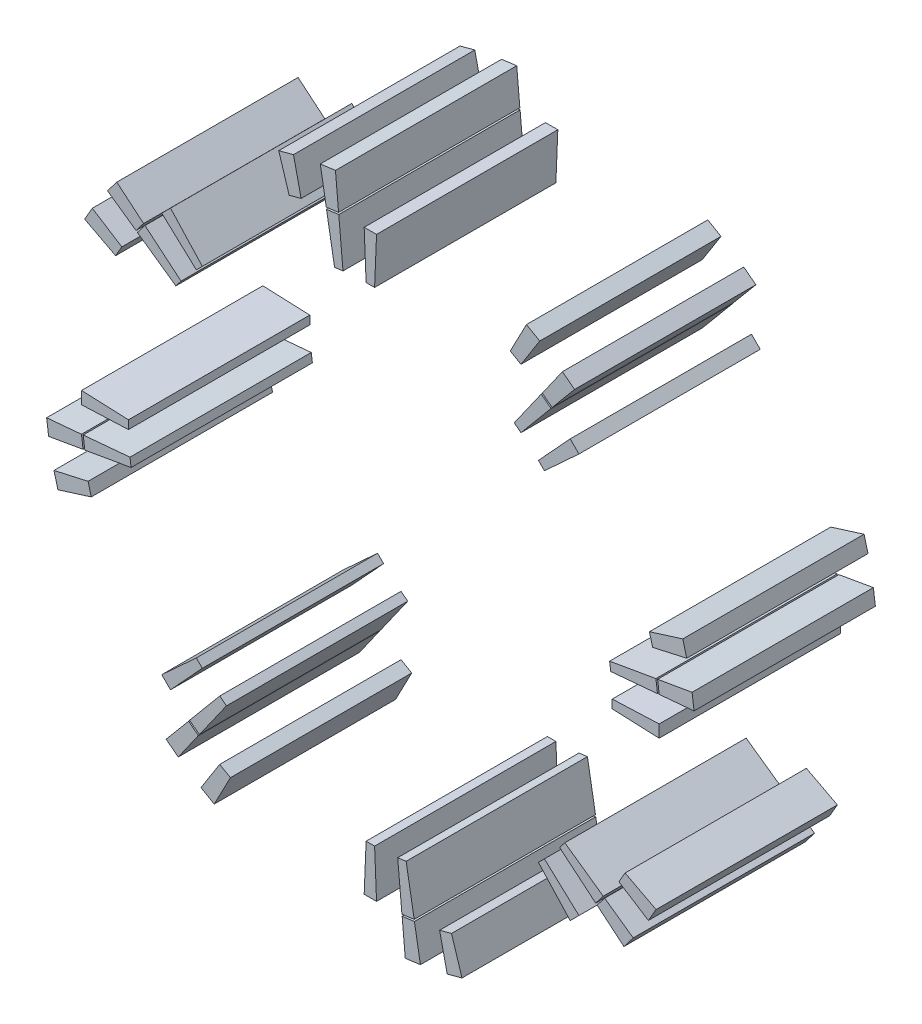
SolidWorks part; units mm, degrees
ref_plane "Спереди" through (0, 0, 0) normal (0, 0, 1) x (1, 0, 0)
ref_plane "Сверху" through (0, 0, 0) normal (0, 1, 0) x (1, 0, 0)
ref_plane "Справа" through (0, 0, 0) normal (1, 0, 0) x (0, 0, -1)
sketch "Эскиз1" plane through (0, 0, 0) normal (0, 0, 1) x (1, 0, 0)
  line L0 (53.3687, -0.9375) -> (63.7231, -1.3648)
  line L1 (63.7231, -1.3648) -> (63.7231, 1.3648)
  line L2 (63.7231, 1.3648) -> (53.3687, 0.9375)
  line L3 (53.3687, 0.9375) -> (53.3687, -0.9375)
  line L4 (63.7382, 7.0147) -> (71.4213, 7.7007)
  line L5 (71.4213, 7.7007) -> (70.9807, 11.0469)
  line L6 (70.9807, 11.0469) -> (63.382, 9.7209)
  line L7 (63.382, 9.7209) -> (63.7382, 7.0147)
  line L8 (53.0345, 6.0365) -> (63.3561, 6.9644)
  line L9 (63.3561, 6.9644) -> (62.9998, 9.6706)
  line L10 (62.9998, 9.6706) -> (52.7897, 7.8955)
  line L11 (52.7897, 7.8955) -> (53.0345, 6.0365)
  line L12 (62.2773, 15.2742) -> (69.8051, 16.9572)
  line L13 (69.8051, 16.9572) -> (68.9316, 20.2172)
  line L14 (68.9316, 20.2172) -> (61.5709, 17.9108)
  line L15 (61.5709, 17.9108) -> (62.2773, 15.2742)
  line L16 (38.4003, 37.0744) -> (46.0241, 44.094)
  line L17 (46.0241, 44.094) -> (44.094, 46.0241)
  line L18 (44.094, 46.0241) -> (37.0744, 38.4003)
  line L19 (37.0744, 38.4003) -> (38.4003, 37.0744)
  line L20 (40.1096, 50.0299) -> (45.0572, 55.9477)
  line L21 (45.0572, 55.9477) -> (42.3797, 58.0023)
  line L22 (42.3797, 58.0023) -> (37.9441, 51.6916)
  line L23 (37.9441, 51.6916) -> (40.1096, 50.0299)
  line L24 (33.2326, 41.7695) -> (39.8749, 49.7241)
  line L25 (39.8749, 49.7241) -> (37.7094, 51.3857)
  line L26 (37.7094, 51.3857) -> (31.745, 42.9109)
  line L27 (31.745, 42.9109) -> (33.2326, 41.7695)
  line L28 (33.2362, 54.8372) -> (37.3691, 61.3502)
  line L29 (37.3691, 61.3502) -> (34.4463, 63.0377)
  line L30 (34.4463, 63.0377) -> (30.8723, 56.202)
  line L31 (30.8723, 56.202) -> (33.2362, 54.8372)
  line L32 (0.9375, 53.3687) -> (1.3648, 63.7231)
  line L33 (1.3648, 63.7231) -> (-1.3648, 63.7231)
  line L34 (-1.3648, 63.7231) -> (-0.9375, 53.3687)
  line L35 (-0.9375, 53.3687) -> (0.9375, 53.3687)
  line L36 (-7.0147, 63.7382) -> (-7.7007, 71.4213)
  line L37 (-7.7007, 71.4213) -> (-11.0469, 70.9807)
  line L38 (-11.0469, 70.9807) -> (-9.7209, 63.382)
  line L39 (-9.7209, 63.382) -> (-7.0147, 63.7382)
  line L40 (-6.0365, 53.0345) -> (-6.9644, 63.3561)
  line L41 (-6.9644, 63.3561) -> (-9.6706, 62.9998)
  line L42 (-9.6706, 62.9998) -> (-7.8955, 52.7897)
  line L43 (-7.8955, 52.7897) -> (-6.0365, 53.0345)
  line L44 (-15.2742, 62.2773) -> (-16.9572, 69.8051)
  line L45 (-16.9572, 69.8051) -> (-20.2172, 68.9316)
  line L46 (-20.2172, 68.9316) -> (-17.9108, 61.5709)
  line L47 (-17.9108, 61.5709) -> (-15.2742, 62.2773)
  line L48 (-37.0744, 38.4003) -> (-44.094, 46.0241)
  line L49 (-44.094, 46.0241) -> (-46.0241, 44.094)
  line L50 (-46.0241, 44.094) -> (-38.4003, 37.0744)
  line L51 (-38.4003, 37.0744) -> (-37.0744, 38.4003)
  line L52 (-50.0299, 40.1096) -> (-55.9477, 45.0572)
  line L53 (-55.9477, 45.0572) -> (-58.0023, 42.3797)
  line L54 (-58.0023, 42.3797) -> (-51.6916, 37.9441)
  line L55 (-51.6916, 37.9441) -> (-50.0299, 40.1096)
  line L56 (-41.7695, 33.2326) -> (-49.7241, 39.8749)
  line L57 (-49.7241, 39.8749) -> (-51.3857, 37.7094)
  line L58 (-51.3857, 37.7094) -> (-42.9109, 31.745)
  line L59 (-42.9109, 31.745) -> (-41.7695, 33.2326)
  line L60 (-54.8372, 33.2362) -> (-61.3502, 37.3691)
  line L61 (-61.3502, 37.3691) -> (-63.0377, 34.4463)
  line L62 (-63.0377, 34.4463) -> (-56.202, 30.8723)
  line L63 (-56.202, 30.8723) -> (-54.8372, 33.2362)
  line L64 (-53.3687, 0.9375) -> (-63.7231, 1.3648)
  line L65 (-63.7231, 1.3648) -> (-63.7231, -1.3648)
  line L66 (-63.7231, -1.3648) -> (-53.3687, -0.9375)
  line L67 (-53.3687, -0.9375) -> (-53.3687, 0.9375)
  line L68 (-63.7382, -7.0147) -> (-71.4213, -7.7007)
  line L69 (-71.4213, -7.7007) -> (-70.9807, -11.0469)
  line L70 (-70.9807, -11.0469) -> (-63.382, -9.7209)
  line L71 (-63.382, -9.7209) -> (-63.7382, -7.0147)
  line L72 (-53.0345, -6.0365) -> (-63.3561, -6.9644)
  line L73 (-63.3561, -6.9644) -> (-62.9998, -9.6706)
  line L74 (-62.9998, -9.6706) -> (-52.7897, -7.8955)
  line L75 (-52.7897, -7.8955) -> (-53.0345, -6.0365)
  line L76 (-62.2773, -15.2742) -> (-69.8051, -16.9572)
  line L77 (-69.8051, -16.9572) -> (-68.9316, -20.2172)
  line L78 (-68.9316, -20.2172) -> (-61.5709, -17.9108)
  line L79 (-61.5709, -17.9108) -> (-62.2773, -15.2742)
  line L80 (-38.4003, -37.0744) -> (-46.0241, -44.094)
  line L81 (-46.0241, -44.094) -> (-44.094, -46.0241)
  line L82 (-44.094, -46.0241) -> (-37.0744, -38.4003)
  line L83 (-37.0744, -38.4003) -> (-38.4003, -37.0744)
  line L84 (-40.1096, -50.0299) -> (-45.0572, -55.9477)
  line L85 (-45.0572, -55.9477) -> (-42.3797, -58.0023)
  line L86 (-42.3797, -58.0023) -> (-37.9441, -51.6916)
  line L87 (-37.9441, -51.6916) -> (-40.1096, -50.0299)
  line L88 (-33.2326, -41.7695) -> (-39.8749, -49.7241)
  line L89 (-39.8749, -49.7241) -> (-37.7094, -51.3857)
  line L90 (-37.7094, -51.3857) -> (-31.745, -42.9109)
  line L91 (-31.745, -42.9109) -> (-33.2326, -41.7695)
  line L92 (-33.2362, -54.8372) -> (-37.3691, -61.3502)
  line L93 (-37.3691, -61.3502) -> (-34.4463, -63.0377)
  line L94 (-34.4463, -63.0377) -> (-30.8723, -56.202)
  line L95 (-30.8723, -56.202) -> (-33.2362, -54.8372)
  line L96 (-0.9375, -53.3687) -> (-1.3648, -63.7231)
  line L97 (-1.3648, -63.7231) -> (1.3648, -63.7231)
  line L98 (1.3648, -63.7231) -> (0.9375, -53.3687)
  line L99 (0.9375, -53.3687) -> (-0.9375, -53.3687)
  line L100 (7.0147, -63.7382) -> (7.7007, -71.4213)
  line L101 (7.7007, -71.4213) -> (11.0469, -70.9807)
  line L102 (11.0469, -70.9807) -> (9.7209, -63.382)
  line L103 (9.7209, -63.382) -> (7.0147, -63.7382)
  line L104 (6.0365, -53.0345) -> (6.9644, -63.3561)
  line L105 (6.9644, -63.3561) -> (9.6706, -62.9998)
  line L106 (9.6706, -62.9998) -> (7.8955, -52.7897)
  line L107 (7.8955, -52.7897) -> (6.0365, -53.0345)
  line L108 (15.2742, -62.2773) -> (16.9572, -69.8051)
  line L109 (16.9572, -69.8051) -> (20.2172, -68.9316)
  line L110 (20.2172, -68.9316) -> (17.9108, -61.5709)
  line L111 (17.9108, -61.5709) -> (15.2742, -62.2773)
  line L112 (37.0744, -38.4003) -> (44.094, -46.0241)
  line L113 (44.094, -46.0241) -> (46.0241, -44.094)
  line L114 (46.0241, -44.094) -> (38.4003, -37.0744)
  line L115 (38.4003, -37.0744) -> (37.0744, -38.4003)
  line L116 (50.0299, -40.1096) -> (55.9477, -45.0572)
  line L117 (55.9477, -45.0572) -> (58.0023, -42.3797)
  line L118 (58.0023, -42.3797) -> (51.6916, -37.9441)
  line L119 (51.6916, -37.9441) -> (50.0299, -40.1096)
  line L120 (41.7695, -33.2326) -> (49.7241, -39.8749)
  line L121 (49.7241, -39.8749) -> (51.3857, -37.7094)
  line L122 (51.3857, -37.7094) -> (42.9109, -31.745)
  line L123 (42.9109, -31.745) -> (41.7695, -33.2326)
  line L124 (54.8372, -33.2362) -> (61.3502, -37.3691)
  line L125 (61.3502, -37.3691) -> (63.0377, -34.4463)
  line L126 (63.0377, -34.4463) -> (56.202, -30.8723)
  line L127 (56.202, -30.8723) -> (54.8372, -33.2362)
extrude "Slot_copper_envelopes" add sketch "Эскиз1" along normal blind 40 from offset 20 separate body
